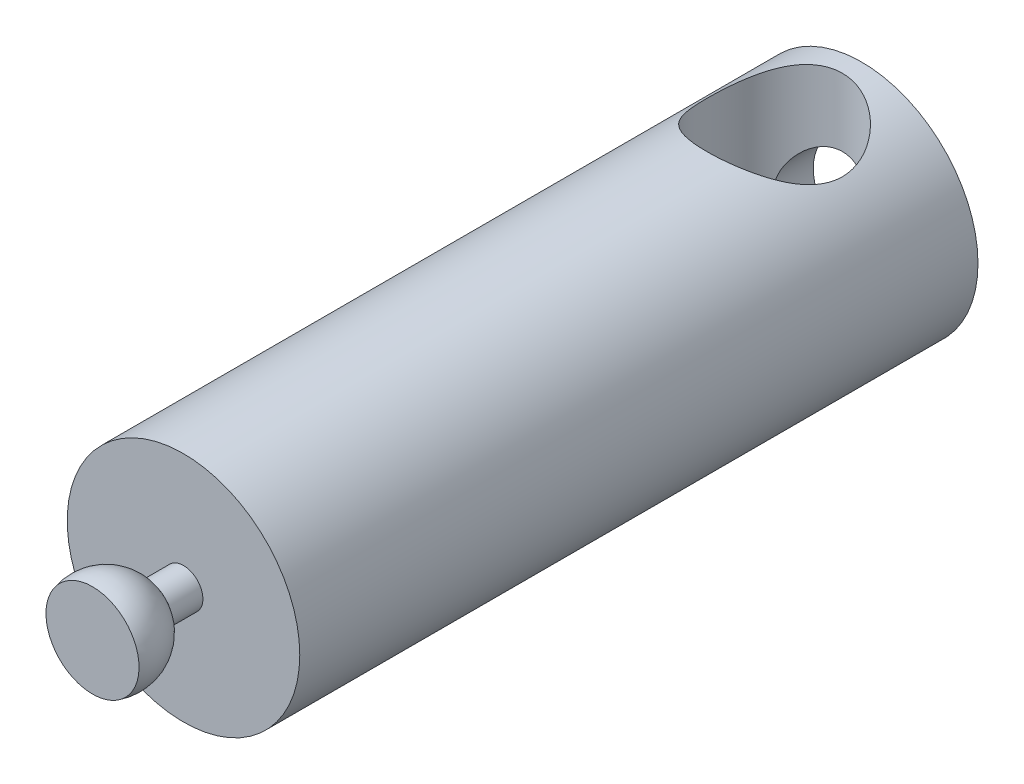
SolidWorks part; units mm, degrees
ref_plane "Face" through (0, 0, 0) normal (0, 0, 1) x (1, 0, 0)
ref_plane "Dessus" through (0, 0, 0) normal (0, 1, 0) x (1, 0, 0)
ref_plane "Droite" through (0, 0, 0) normal (1, 0, 0) x (0, 0, -1)
sketch "Esquisse1" plane through (0, 0, 0) normal (0, 0, 1) x (1, 0, 0)
  circle A0 centre (0, 0) radius 6
  dimension "D1" = 12
extrude "Base-Extrusion" add sketch "Esquisse1" along normal blind 35
sketch "Esquisse2" plane through (0, 0, 0) normal (0, 1, 0) x (1, 0, 0)
  line L0 (0, -35) -> (0, 0) construction
  circle A0 centre (0, -4.5) radius 3.5
  dimension "D1" = 7
  dimension "D2" = 4.5
extrude "Enlèv. mat.-Extru.1" cut sketch "Esquisse2" against normal mid plane 35
sketch "Esquisse3" plane through (0, 0, 0) normal (0, 0, -1) x (-1, 0, 0)
  circle A0 centre (0, 0) radius 2.5
  dimension "D1" = 5
extrude "Enlèv. mat.-Extru.2" cut sketch "Esquisse3" against normal blind 8
sketch "Esquisse4" plane through (0, 0, 8) normal (0, 0, -1) x (-1, 0, 0)
  circle A0 centre (0, 0) radius 1
  dimension "D1" = 2
extrude "Boss.-Extru.1" add sketch "Esquisse4" along normal blind 3.5
sketch "Esquisse5" plane through (0, 0, 0) normal (1, 0, 0) x (0, 0, -1)
  line L0 (-31.9127, 0) -> (-46.8519, 0) construction
  line L1 (-35, 0) -> (0, 0) construction
  line L2 (-35, 6) -> (-35, -6) construction
  line L3 (-35, 1) -> (-36.7087, 1)
  line L4 (-35, 1) -> (-35, 0)
  line L5 (-39.6955, 0) -> (-35, 0)
  line L6 (-39.6955, 2.4013) -> (-39.6955, 0)
  arc A0 (-36.7087, 1) -> (-39.6955, 2.4013) centre (-39, 0) ccw
  dimension "D1" = 5
  dimension "D2" = 1
  dimension "D3" = 4
revolve "Boss.-Révol.1" add sketch "Esquisse5" angle 360 about L0
